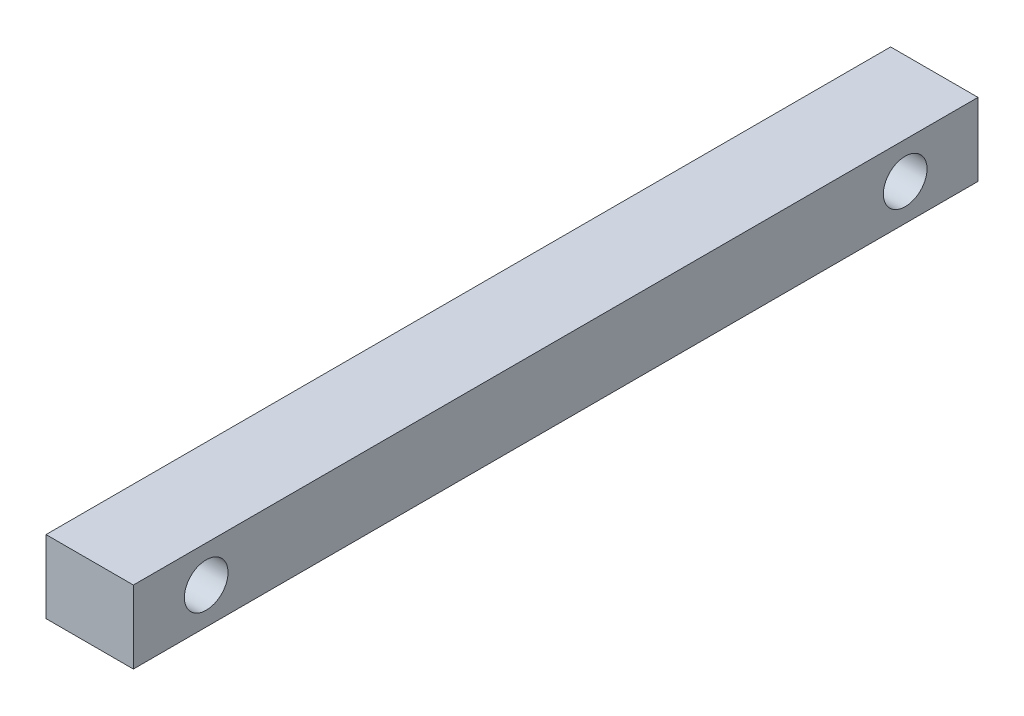
SolidWorks part; units mm, degrees
ref_plane "Plano frontal" through (0, 0, 0) normal (0, 0, 1) x (1, 0, 0)
ref_plane "Plano superior" through (0, 0, 0) normal (0, 1, 0) x (1, 0, 0)
ref_plane "Plano direito" through (0, 0, 0) normal (1, 0, 0) x (0, 0, -1)
sketch "Esboço1" plane through (0, 0, 0) normal (0, 0, 1) x (1, 0, 0)
  line L5 (15, -12.5) -> (-15, -12.5)
  line L6 (15, -12.5) -> (15, 12.5)
  line L11 (15, 12.5) -> (-15, 12.5)
  line L12 (-15, -12.5) -> (-15, 12.5)
  line L13 (15, -12.5) -> (-15, 12.5) construction
  line L14 (15, 12.5) -> (-15, -12.5) construction
  point P0 (0, 0)
  dimension "D1" = 25
  dimension "D2" = 30
extrude "Ressalto-extrusão2" add sketch "Esboço1" along normal blind 290
sketch "Esboço2" plane through (-15, 0, 0) normal (-1, 0, 0) x (0, 0, 1)
  line L0 (0, 0) -> (25, 0)
  line L1 (280.9096, 5.6742) -> (290, 0)
  line L2 (290, 12.5) -> (290, -12.5) construction
  line L3 (290, 0) -> (270, 0)
  line L4 (270, 0) -> (265, 0)
  circle A0 centre (25, 0) radius 7.5
  circle A1 centre (265, 0) radius 7.5
  dimension "D2" = 15
  dimension "D5" = 15
  dimension "D1" = 25
  dimension "D3" = 20
  dimension "D4" = 5
extrude "Corte-extrusão1" cut sketch "Esboço2" against normal blind 290
sketch "Esboço3" plane through (0, 0, 290) normal (0, 0, 1) x (1, 0, 0)
